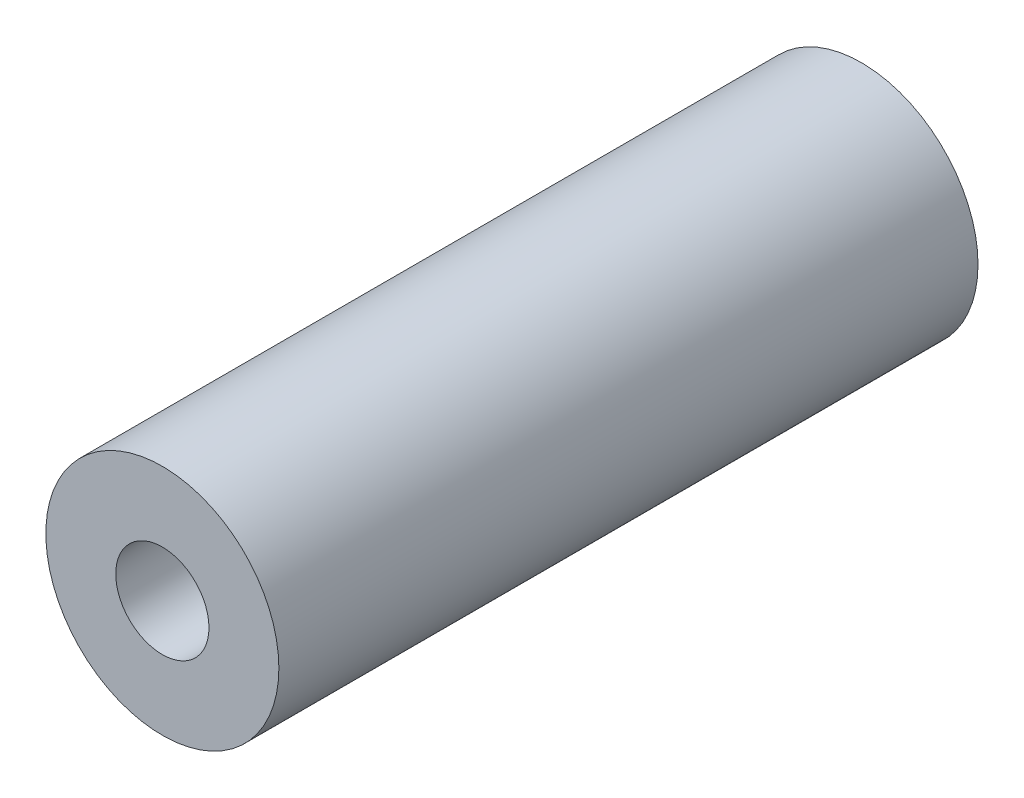
SolidWorks part; units mm, degrees
ref_plane "Front Plane" through (0, 0, 0) normal (0, 0, 1) x (1, 0, 0)
ref_plane "Top Plane" through (0, 0, 0) normal (0, 1, 0) x (1, 0, 0)
ref_plane "Right Plane" through (0, 0, 0) normal (1, 0, 0) x (0, 0, -1)
sketch "Standoff_OD8_ID3p2_profile" plane through (0, 0, 0) normal (0, 0, 1) x (1, 0, 0)
  circle A0 centre (0, 0) radius 4
  circle A1 centre (0, 0) radius 1.6
  dimension "D1" = 8
  dimension "D2" = 3.2
extrude "Standoff_OD8_ID3p2" add sketch "Standoff_OD8_ID3p2_profile" along normal blind 24
